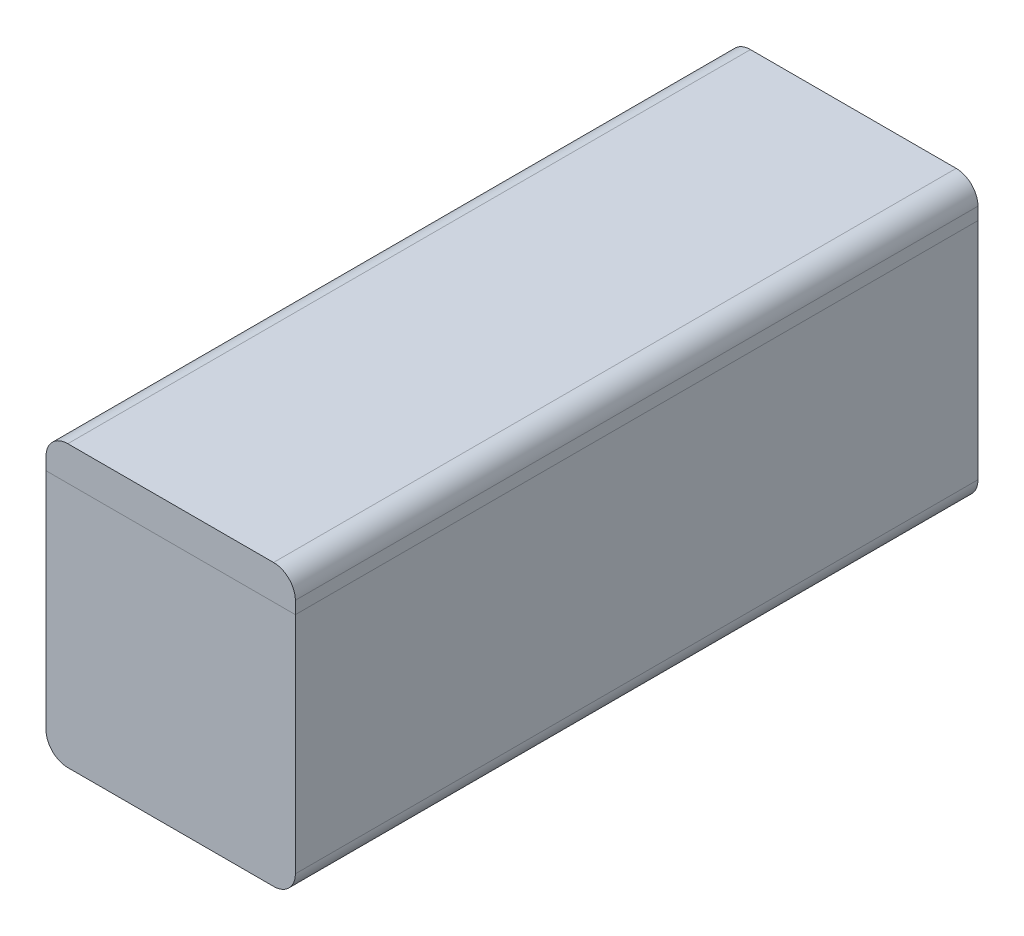
SolidWorks part; units mm, degrees
ref_plane "Front Plane" through (0, 0, 0) normal (0, 0, 1) x (1, 0, 0)
ref_plane "Top Plane" through (0, 0, 0) normal (0, 1, 0) x (1, 0, 0)
ref_plane "Right Plane" through (0, 0, 0) normal (1, 0, 0) x (0, 0, -1)
sketch "Sketch2" plane through (0, 0, 0) normal (0, 0, 1) x (1, 0, 0)
  line L1 (7, 0) -> (73, 0)
  line L2 (0, 7) -> (0, 83)
  line L3 (7, 90) -> (73, 90)
  line L4 (80, 7) -> (80, 83)
  arc A0 (73, 90) -> (80, 83) centre (73, 83) cw
  arc A1 (73, 0) -> (80, 7) centre (73, 7) ccw
  arc A2 (7, 0) -> (0, 7) centre (7, 7) cw
  arc A3 (0, 83) -> (7, 90) centre (7, 83) cw
  point P7 (80, 90)
  point P12 (0, 0)
  point P15 (0, 90)
  dimension "D3" = 7
  dimension "D1" = 90
  dimension "D2" = 80
extrude "Boss-Extrude1" add sketch "Sketch2" against normal blind 219
shell "Shell1" thickness 2
sketch "Sketch3" plane through (0, 0, 0) normal (0, 0, 1) x (1, 0, 0)
  line L0 (0, 79) -> (80, 79)
  line L1 (0, 83) -> (0, 7) construction
  line L3 (73, 90) -> (7, 90) construction
  line L4 (80, 7) -> (80, 83) construction
  dimension "D1" = 11
split "Split1" trim tools "Sketch3" bodies to split 101 resulting bodies 102 103
